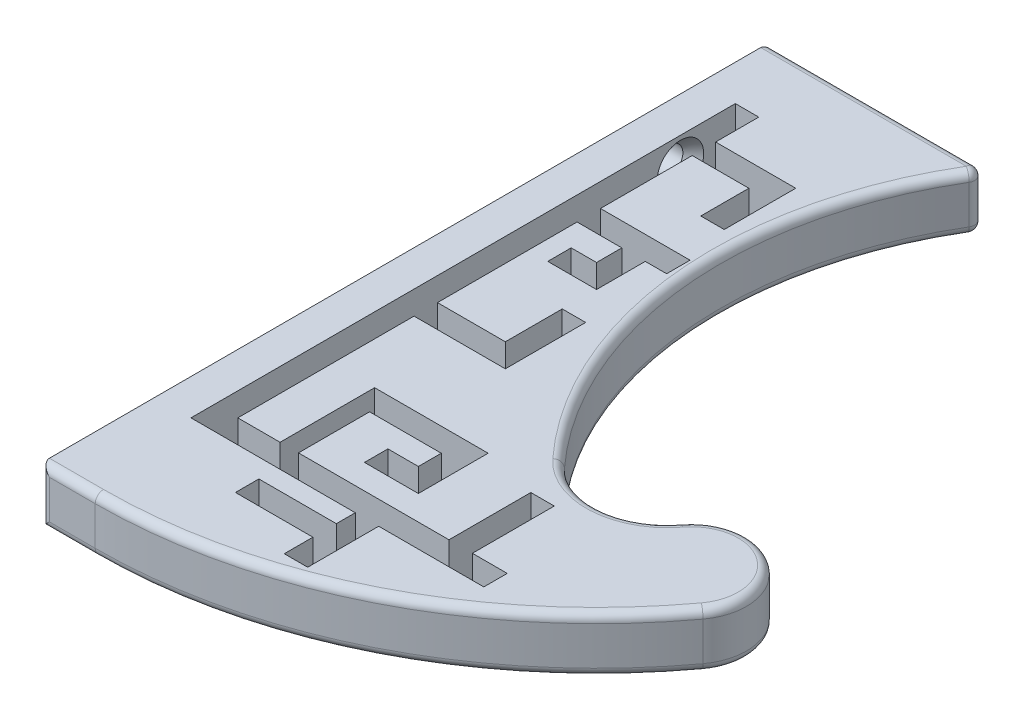
SolidWorks part; units mm, degrees
ref_plane "Front Plane" through (0, 0, 0) normal (0, 0, 1) x (1, 0, 0)
ref_plane "Top Plane" through (0, 0, 0) normal (0, 1, 0) x (1, 0, 0)
ref_plane "Right Plane" through (0, 0, 0) normal (1, 0, 0) x (0, 0, -1)
sketch "Sketch1" plane through (0, 0, 0) normal (0, 1, 0) x (1, 0, 0)
  line L0 (0, 0) -> (0, 132) construction
  line L2 (0, 0) -> (9.8069, 0)
  line L3 (0, 0) -> (0, 132)
  line L4 (0, 132) -> (40, 132)
  line L5 (6.5, 119.4) -> (10.75, 119.4)
  line L6 (6.5, 119.4) -> (6.5, 20.671)
  line L7 (6.5, 20.671) -> (10.75, 20.671)
  line L8 (10.75, 119.4) -> (10.75, 20.671)
  line L9 (10.75, 111.5743) -> (25.2764, 111.5743)
  line L10 (10.75, 111.5743) -> (10.75, 107.3243)
  line L11 (10.75, 107.3243) -> (25.2764, 107.3243)
  line L12 (25.2764, 111.5743) -> (25.2764, 107.3243)
  line L13 (25.2764, 107.3243) -> (21.0264, 107.3243)
  line L14 (25.2764, 107.3243) -> (25.2764, 98.6072)
  line L15 (25.2764, 98.6072) -> (21.0264, 98.6072)
  line L16 (21.0264, 107.3243) -> (21.0264, 98.6072)
  line L17 (10.75, 90.6927) -> (26.9957, 90.6927)
  line L18 (10.75, 90.6927) -> (10.75, 86.4427)
  line L19 (10.75, 86.4427) -> (26.9957, 86.4427)
  line L20 (26.9957, 90.6927) -> (26.9957, 86.4427)
  line L21 (18.8728, 86.4427) -> (23.1228, 86.4427)
  line L22 (18.8728, 86.4427) -> (18.8728, 77.6023)
  line L23 (18.8728, 77.6023) -> (23.1228, 77.6023)
  line L24 (23.1228, 86.4427) -> (23.1228, 77.6023)
  line L25 (18.8728, 77.6023) -> (14.2758, 77.6023)
  line L26 (18.8728, 77.6023) -> (18.8728, 81.8523)
  line L27 (18.8728, 81.8523) -> (14.2758, 81.8523)
  line L28 (14.2758, 77.6023) -> (14.2758, 81.8523)
  line L29 (10.75, 61.1302) -> (27.3059, 61.1302)
  line L30 (10.75, 61.1302) -> (10.75, 56.8802)
  line L31 (10.75, 56.8802) -> (27.3059, 56.8802)
  line L32 (27.3059, 61.1302) -> (27.3059, 56.8802)
  line L33 (27.3059, 61.1302) -> (23.0559, 61.1302)
  line L34 (27.3059, 61.1302) -> (27.3059, 71.4493)
  line L35 (27.3059, 71.4493) -> (23.0559, 71.4493)
  line L36 (23.0559, 61.1302) -> (23.0559, 71.4493)
  line L37 (10.75, 20.671) -> (59.6087, 20.671)
  line L38 (10.75, 20.671) -> (10.75, 24.921)
  line L39 (10.75, 24.921) -> (59.6087, 24.921)
  line L40 (59.6087, 20.671) -> (59.6087, 24.921)
  line L41 (40.5487, 20.671) -> (36.2987, 20.671)
  line L42 (40.5487, 20.671) -> (40.5487, 7.7922)
  line L43 (40.5487, 7.7922) -> (36.2987, 7.7922)
  line L44 (36.2987, 20.671) -> (36.2987, 7.7922)
  line L45 (36.2987, 17.2364) -> (22.2499, 17.2364)
  line L46 (36.2987, 17.2364) -> (36.2987, 12.9864)
  line L47 (36.2987, 12.9864) -> (22.2499, 12.9864)
  line L48 (22.2499, 17.2364) -> (22.2499, 12.9864)
  line L49 (18.4129, 24.921) -> (21.7499, 24.921)
  line L50 (18.4129, 24.921) -> (18.4129, 42.0668)
  line L51 (18.4129, 42.0668) -> (21.7499, 42.0668)
  line L52 (21.7499, 24.921) -> (21.7499, 42.0668)
  line L53 (21.7499, 42.0668) -> (39.0031, 42.0668)
  line L54 (21.7499, 42.0668) -> (21.7499, 37.8168)
  line L55 (21.7499, 37.8168) -> (39.0031, 37.8168)
  line L56 (39.0031, 42.0668) -> (39.0031, 37.8168)
  line L57 (39.0031, 37.8168) -> (34.7531, 37.8168)
  line L58 (39.0031, 37.8168) -> (39.0031, 29.4088)
  line L59 (39.0031, 29.4088) -> (34.7531, 29.4088)
  line L60 (34.7531, 37.8168) -> (34.7531, 29.4088)
  line L61 (34.7531, 29.4088) -> (29.2296, 29.4088)
  line L62 (34.7531, 29.4088) -> (34.7531, 33.6588)
  line L63 (34.7531, 33.6588) -> (29.2296, 33.6588)
  line L64 (29.2296, 29.4088) -> (29.2296, 33.6588)
  line L65 (49.0433, 24.921) -> (53.2933, 24.921)
  line L66 (49.0433, 24.921) -> (49.0433, 39.7665)
  line L67 (49.0433, 39.7665) -> (53.2933, 39.7665)
  line L68 (53.2933, 24.921) -> (53.2933, 39.7665)
  arc A3 (83.0485, 36.9939) -> (67.0494, 48.9939) centre (75, 42.9286) ccw
  arc A5 (67.0494, 48.9939) -> (46.8198, 48.0852) centre (56.5545, 57) cw
  arc A6 (46.8198, 48.0852) -> (40, 132) centre (97.4301, 94.4328) cw
  arc A7 (9.8069, 0) -> (83.0485, 36.9939) centre (9.8069, 91) ccw
  dimension "D4" = 75
  dimension "D5" = 91
  dimension "D6" = 20
  dimension "D7" = 4.25
  dimension "D8" = 75
  dimension "D9" = 13.2
  dimension "D3" = 12
  dimension "D1" = 132
  dimension "D2" = 40
  dimension "D10" = 20.25
  dimension "D13" = 6.5
  dimension "D14" = 4.25
  dimension "D15" = 4.25
  dimension "D16" = 4.25
  dimension "D17" = 4.25
  dimension "D18" = 4.25
  dimension "D19" = 4.25
  dimension "D20" = 4.25
  dimension "D21" = 4.25
  dimension "D22" = 4.25
  dimension "D23" = 4.25
  dimension "D24" = 4.25
  dimension "D25" = 4.25
  dimension "D26" = 4.25
  dimension "D27" = 4.25
extrude "Boss-Extrude1" add sketch "Sketch1" along normal blind 10
fillet "Fillet1" radius 1.5 15 edges at (0, 5, 0) (4.9034, 10, 0) (4.9034, 0, 0) (50.834, 10, -9.7733) (50.834, 0, -9.7733) (81.0002, 10, -50.9284) (81.0002, 0, -50.9284) (57.1469, 10, -43.8133) (57.1469, 0, -43.8133) (29.0297, 10, -88.8739) (29.0297, 0, -88.8739) (40, 5, -132) (20, 10, -132) (0, 5, -132) (20, 0, -132)
sketch "Sketch4" plane through (6.5, 0, 0) normal (1, 0, 0) x (0, 0, -1)
  line L0 (107.3243, 10) -> (107.3243, 0) construction
  line L1 (111.5743, 10) -> (111.5743, 0) construction
  line L2 (107.3243, 10) -> (107.3243, 0) construction
  line L3 (111.5743, 10) -> (111.5743, 0) construction
  line L4 (111.5743, 0) -> (107.3243, 0) construction
  line L5 (107.3243, 0) -> (109.4493, 0)
  line L6 (109.4493, 0) -> (109.4493, 10) construction
  point P6 (109.4493, 5)
hole_wizard "CSK for #8 Flat Head Machine Screw2" positions "3DSketch3" profile "Sketch5" countersink size "#8" standard "ANSI Inch"
sketch3d "3DSketch3"
  point P0 (6.5, 5, -109.4493)
sketch "Sketch5" plane through (6.5, 5, -109.4493) normal (0, 1, 0) x (0, 0, -1)
  line L0 (0, 0) -> (0, 11.4766)
  line L1 (0, 11.4766) -> (2.4574, 10)
  line L2 (2.4574, 10) -> (2.4574, 2.0234)
  line L3 (2.4574, 2.0234) -> (4.2164, 0)
  line L5 (4.2164, 0) -> (0, 0)
  line L6 (-2.4574, 2.0234) -> (-4.2164, 0) construction
  line L10 (0, 11.4766) -> (-2.4575, 10) construction
  line L11 (0, -6.35) -> (0, 107.95) construction
  dimension "Hole Dia." = 4.9149
  dimension "Hole Depth" = 10
  dimension "Near C'Sink Dia." = 8.4328
  dimension "Near C'Sink Angle" = 82
  dimension "Drill Angle" = 118
